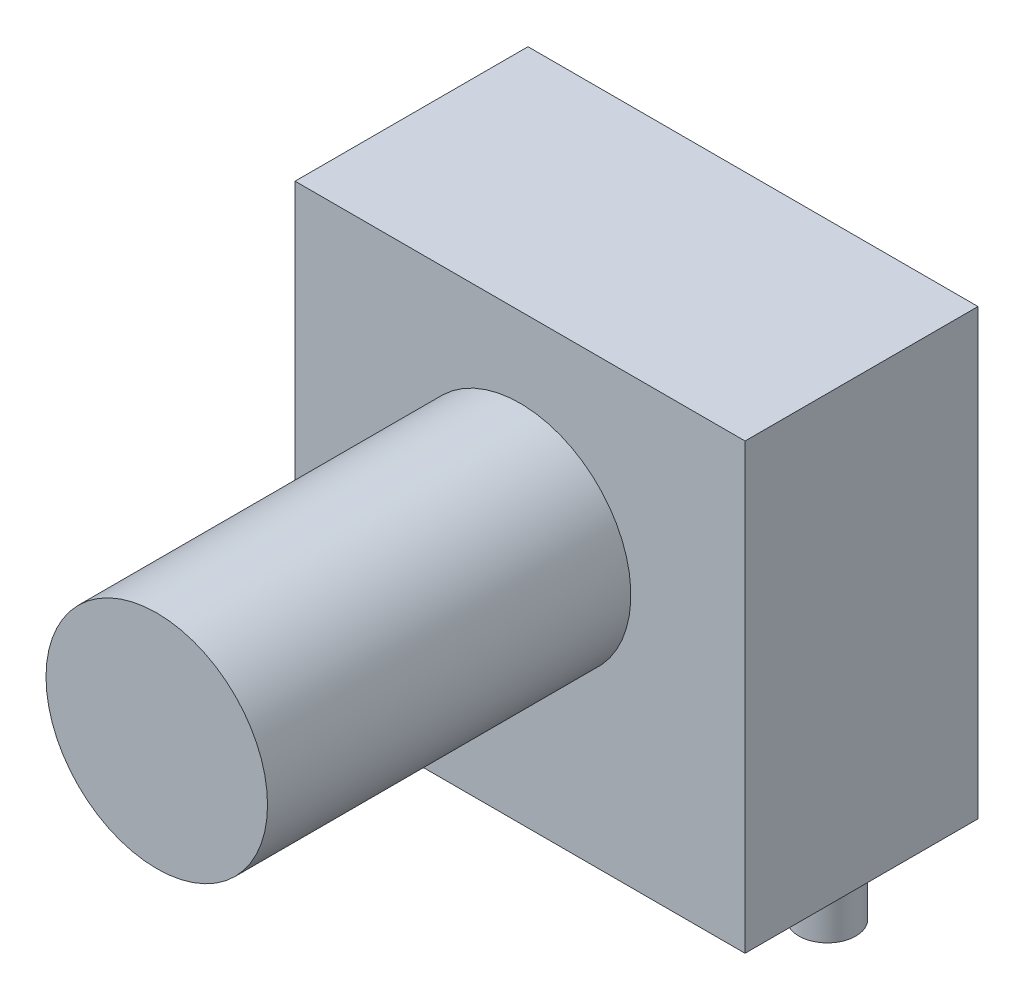
SolidWorks part; units mm, degrees
ref_plane "Front Plane" through (0, 0, 0) normal (0, 0, 1) x (1, 0, 0)
ref_plane "Top Plane" through (0, 0, 0) normal (0, 1, 0) x (1, 0, 0)
ref_plane "Right Plane" through (0, 0, 0) normal (1, 0, 0) x (0, 0, -1)
sketch "Sketch1" plane through (0, 0, 0) normal (0, 1, 0) x (1, 0, 0)
  line L1 (-3.555, -1.84) -> (3.555, -1.84)
  line L2 (-3.555, -1.84) -> (-3.555, 1.84)
  line L3 (-3.555, 1.84) -> (3.555, 1.84)
  line L4 (3.555, -1.84) -> (3.555, 1.84)
  line L5 (-3.555, -1.84) -> (3.555, 1.84) construction
  line L6 (-3.555, 1.84) -> (3.555, -1.84) construction
  point P0 (0, 0)
  dimension "D1" = 7.11
  dimension "D2" = 3.68
extrude "Boss-Extrude1" add sketch "Sketch1" along normal blind 7.01
sketch "Sketch2" plane through (0, 0, 1.84) normal (0, 0, 1) x (1, 0, 0)
  circle A0 centre (0, 4) radius 1.75
  dimension "D2" = 3.5
  dimension "D1" = 4
extrude "Boss-Extrude2" add sketch "Sketch2" along normal blind 5.74
sketch "Sketch3" plane through (0, 0, 0) normal (0, 1, 0) x (1, 0, 0)
  line L0 (-1.75, -7.58) -> (1.75, -7.58) construction
  line L1 (-3.555, 1.84) -> (-3.555, -1.84) construction
  line L2 (3.555, -1.84) -> (3.555, 1.84) construction
  circle A2 centre (-2.245, 0.77) radius 0.45
  circle A3 centre (2.245, 0.77) radius 0.45
  dimension "D1" = 0.9
  dimension "D2" = 0.9
  dimension "D3" = 8.35
  dimension "D4" = 8.35
  dimension "D5" = 1.31
  dimension "D6" = 1.31
extrude "Boss-Extrude3" add sketch "Sketch3" against normal blind 1.5
